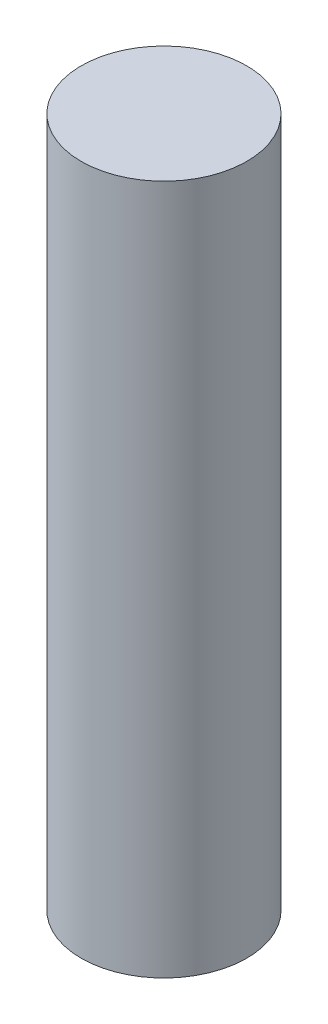
SolidWorks part; units mm, degrees
ref_plane "Front Plane" through (0, 0, 0) normal (0, 0, 1) x (1, 0, 0)
ref_plane "Top Plane" through (0, 0, 0) normal (0, 1, 0) x (1, 0, 0)
ref_plane "Right Plane" through (0, 0, 0) normal (1, 0, 0) x (0, 0, -1)
sketch "Sketch1" plane through (0, 0, 0) normal (0, 1, 0) x (1, 0, 0)
  circle A0 centre (0, 0) radius 0.6
  dimension "D1" = 1.2
extrude "Boss-Extrude1" add sketch "Sketch1" along normal blind 5
